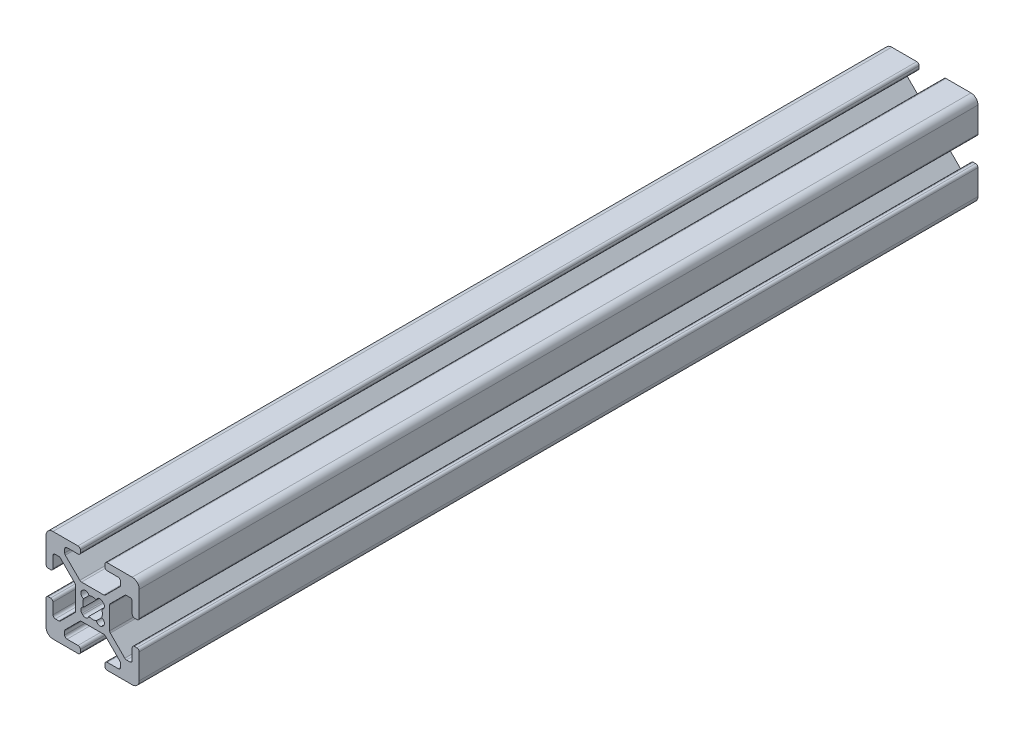
SolidWorks part; units mm, degrees
material "6105-T5 Aluminum"
ref_plane "Front Plane" through (0, 0, 0) normal (0, 0, 1) x (1, 0, 0)
ref_plane "Top Plane" through (0, 0, 0) normal (0, 1, 0) x (1, 0, 0)
ref_plane "Right Plane" through (0, 0, 0) normal (1, 0, 0) x (0, 0, -1)
sketch "Sketch1" plane through (0, 0, 0) normal (0, 0, 1) x (1, 0, 0)
  line L0 (9.492, 2.63) -> (9.008, 2.63)
  line L1 (8.5, 3.138) -> (8.5, 5.487)
  line L2 (10, 3.138) -> (10, 8.5)
  line L3 (3.655, -2.3839) -> (3.655, 2.3839)
  line L4 (7.2661, 5.995) -> (7.992, 5.995)
  line L5 (6.9069, 5.8462) -> (3.8038, 2.7431)
  line L6 (9.492, -2.63) -> (9.008, -2.63)
  line L7 (10, -3.138) -> (10, -8.5)
  line L8 (8.5, -3.138) -> (8.5, -5.487)
  line L9 (7.2661, -5.995) -> (7.992, -5.995)
  line L10 (6.9069, -5.8462) -> (3.8038, -2.7431)
  line L11 (2.1249, -2.3045) -> (2.3045, -2.1249)
  line L12 (-2.63, 9.492) -> (-2.63, 9.008)
  line L13 (-3.138, 10) -> (-8.5, 10)
  line L14 (-3.138, 8.5) -> (-5.487, 8.5)
  line L15 (2.3839, 3.655) -> (-2.3839, 3.655)
  line L16 (-5.995, 7.2661) -> (-5.995, 7.992)
  line L17 (-5.8462, 6.9069) -> (-2.7431, 3.8038)
  line L18 (2.63, 9.492) -> (2.63, 9.008)
  line L19 (3.138, 10) -> (8.5, 10)
  line L20 (3.138, 8.5) -> (5.487, 8.5)
  line L21 (5.995, 7.2661) -> (5.995, 7.992)
  line L22 (5.8462, 6.9069) -> (2.7431, 3.8038)
  line L23 (2.3045, 2.1249) -> (2.1249, 2.3045)
  line L24 (-9.492, -2.63) -> (-9.008, -2.63)
  line L25 (-10, -3.138) -> (-10, -8.5)
  line L26 (-8.5, -3.138) -> (-8.5, -5.487)
  line L27 (-3.655, 2.3839) -> (-3.655, -2.3839)
  line L28 (-7.2661, -5.995) -> (-7.992, -5.995)
  line L29 (-6.9069, -5.8462) -> (-3.8038, -2.7431)
  line L30 (-9.492, 2.63) -> (-9.008, 2.63)
  line L31 (-10, 3.138) -> (-10, 8.5)
  line L32 (-8.5, 3.138) -> (-8.5, 5.487)
  line L33 (-7.2661, 5.995) -> (-7.992, 5.995)
  line L34 (-6.9069, 5.8462) -> (-3.8038, 2.7431)
  line L35 (-2.1249, 2.3045) -> (-2.3045, 2.1249)
  line L36 (2.63, -9.492) -> (2.63, -9.008)
  line L37 (3.138, -10) -> (8.5, -10)
  line L38 (3.138, -8.5) -> (5.487, -8.5)
  line L39 (-2.3839, -3.655) -> (2.3839, -3.655)
  line L40 (5.995, -7.2661) -> (5.995, -7.992)
  line L41 (5.8462, -6.9069) -> (2.7431, -3.8038)
  line L42 (-2.63, -9.492) -> (-2.63, -9.008)
  line L43 (-3.138, -10) -> (-8.5, -10)
  line L44 (-3.138, -8.5) -> (-5.487, -8.5)
  line L45 (-5.995, -7.2661) -> (-5.995, -7.992)
  line L46 (-5.8462, -6.9069) -> (-2.7431, -3.8038)
  line L47 (-2.3045, -2.1249) -> (-2.1249, -2.3045)
  arc A0 (-0.804, -1.9351) -> (0.804, -1.9351) centre (0, 0) ccw
  arc A1 (8.5, 5.487) -> (7.992, 5.995) centre (7.992, 5.487) ccw
  arc A2 (7.2661, 5.995) -> (6.9069, 5.8462) centre (7.2661, 5.487) ccw
  arc A3 (3.8038, 2.7431) -> (3.655, 2.3839) centre (4.163, 2.3839) ccw
  arc A4 (3.655, -2.3839) -> (3.8038, -2.7431) centre (4.163, -2.3839) ccw
  arc A5 (6.9069, -5.8462) -> (7.2661, -5.995) centre (7.2661, -5.487) ccw
  arc A6 (7.992, -5.995) -> (8.5, -5.487) centre (7.992, -5.487) ccw
  arc A7 (9.008, -2.63) -> (8.5, -3.138) centre (9.008, -3.138) ccw
  arc A8 (10, -3.138) -> (9.492, -2.63) centre (9.492, -3.138) ccw
  arc A9 (9.492, 2.63) -> (10, 3.138) centre (9.492, 3.138) ccw
  arc A10 (8.5, 3.138) -> (9.008, 2.63) centre (9.008, 3.138) ccw
  arc A11 (0.804, -1.9351) -> (2.1249, -2.3045) centre (1.5684, -1.748) ccw
  arc A12 (2.3045, -2.1249) -> (1.9351, -0.804) centre (1.748, -1.5684) ccw
  arc A13 (-2.63, 9.492) -> (-3.138, 10) centre (-3.138, 9.492) ccw
  arc A14 (-3.138, 8.5) -> (-2.63, 9.008) centre (-3.138, 9.008) ccw
  arc A15 (1.9351, -0.804) -> (1.9351, 0.804) centre (0, 0) ccw
  arc A16 (-2.7431, 3.8038) -> (-2.3839, 3.655) centre (-2.3839, 4.163) ccw
  arc A17 (-5.487, 8.5) -> (-5.995, 7.992) centre (-5.487, 7.992) ccw
  arc A18 (-5.995, 7.2661) -> (-5.8462, 6.9069) centre (-5.487, 7.2661) ccw
  arc A19 (2.63, 9.008) -> (3.138, 8.5) centre (3.138, 9.008) ccw
  arc A20 (3.138, 10) -> (2.63, 9.492) centre (3.138, 9.492) ccw
  arc A21 (5.995, 7.992) -> (5.487, 8.5) centre (5.487, 7.992) ccw
  arc A22 (5.8462, 6.9069) -> (5.995, 7.2661) centre (5.487, 7.2661) ccw
  arc A23 (2.3839, 3.655) -> (2.7431, 3.8038) centre (2.3839, 4.163) ccw
  arc A24 (1.9351, 0.804) -> (2.3045, 2.1249) centre (1.748, 1.5684) ccw
  arc A25 (2.1249, 2.3045) -> (0.804, 1.9351) centre (1.5684, 1.748) ccw
  arc A26 (-9.492, -2.63) -> (-10, -3.138) centre (-9.492, -3.138) ccw
  arc A27 (-8.5, -3.138) -> (-9.008, -2.63) centre (-9.008, -3.138) ccw
  arc A28 (0.804, 1.9351) -> (-0.804, 1.9351) centre (0, 0) ccw
  arc A29 (-3.8038, -2.7431) -> (-3.655, -2.3839) centre (-4.163, -2.3839) ccw
  arc A30 (-8.5, -5.487) -> (-7.992, -5.995) centre (-7.992, -5.487) ccw
  arc A31 (-7.2661, -5.995) -> (-6.9069, -5.8462) centre (-7.2661, -5.487) ccw
  arc A32 (-9.008, 2.63) -> (-8.5, 3.138) centre (-9.008, 3.138) ccw
  arc A33 (-10, 3.138) -> (-9.492, 2.63) centre (-9.492, 3.138) ccw
  arc A34 (-7.992, 5.995) -> (-8.5, 5.487) centre (-7.992, 5.487) ccw
  arc A35 (-6.9069, 5.8462) -> (-7.2661, 5.995) centre (-7.2661, 5.487) ccw
  arc A36 (-3.655, 2.3839) -> (-3.8038, 2.7431) centre (-4.163, 2.3839) ccw
  arc A37 (-0.804, 1.9351) -> (-2.1249, 2.3045) centre (-1.5684, 1.748) ccw
  arc A38 (-2.3045, 2.1249) -> (-1.9351, 0.804) centre (-1.748, 1.5684) ccw
  arc A39 (2.63, -9.492) -> (3.138, -10) centre (3.138, -9.492) ccw
  arc A40 (3.138, -8.5) -> (2.63, -9.008) centre (3.138, -9.008) ccw
  arc A41 (-1.9351, 0.804) -> (-1.9351, -0.804) centre (0, 0) ccw
  arc A42 (2.7431, -3.8038) -> (2.3839, -3.655) centre (2.3839, -4.163) ccw
  arc A43 (5.487, -8.5) -> (5.995, -7.992) centre (5.487, -7.992) ccw
  arc A44 (5.995, -7.2661) -> (5.8462, -6.9069) centre (5.487, -7.2661) ccw
  arc A45 (-2.63, -9.008) -> (-3.138, -8.5) centre (-3.138, -9.008) ccw
  arc A46 (-3.138, -10) -> (-2.63, -9.492) centre (-3.138, -9.492) ccw
  arc A47 (-5.995, -7.992) -> (-5.487, -8.5) centre (-5.487, -7.992) ccw
  arc A48 (-5.8462, -6.9069) -> (-5.995, -7.2661) centre (-5.487, -7.2661) ccw
  arc A49 (-2.3839, -3.655) -> (-2.7431, -3.8038) centre (-2.3839, -4.163) ccw
  arc A50 (-1.9351, -0.804) -> (-2.3045, -2.1249) centre (-1.748, -1.5684) ccw
  arc A51 (-2.1249, -2.3045) -> (-0.804, -1.9351) centre (-1.5684, -1.748) ccw
  arc A52 (10, 8.5) -> (8.5, 10) centre (8.5, 8.5) ccw
  arc A53 (8.5, -10) -> (10, -8.5) centre (8.5, -8.5) ccw
  arc A54 (-10, -8.5) -> (-8.5, -10) centre (-8.5, -8.5) ccw
  arc A55 (-8.5, 10) -> (-10, 8.5) centre (-8.5, 8.5) ccw
extrude "Extrude1" add sketch "Sketch1" against normal blind 180
sketch "Sketch2" plane through (0, 3.655, 0) normal (0, 1, 0) x (1, 0, 0)
  line L0 (2.3839, 180) -> (-2.3839, 180) construction
  line L1 (2.3839, 180) -> (2.3839, 0) construction
  line L2 (2.3839, 0) -> (-2.3839, 0) construction
  line L3 (0, 170) -> (0, 180) construction
  line L4 (0, 10) -> (0, 0) construction
  circle A0 centre (0, 170) radius 2.5
  circle A1 centre (0, 10) radius 2.5
  dimension "D1" = 5
  dimension "D3" = 5
  dimension "D2" = 10
  dimension "D4" = 10
extrude "Cut-Extrude1" cut sketch "Sketch2" against normal through all
